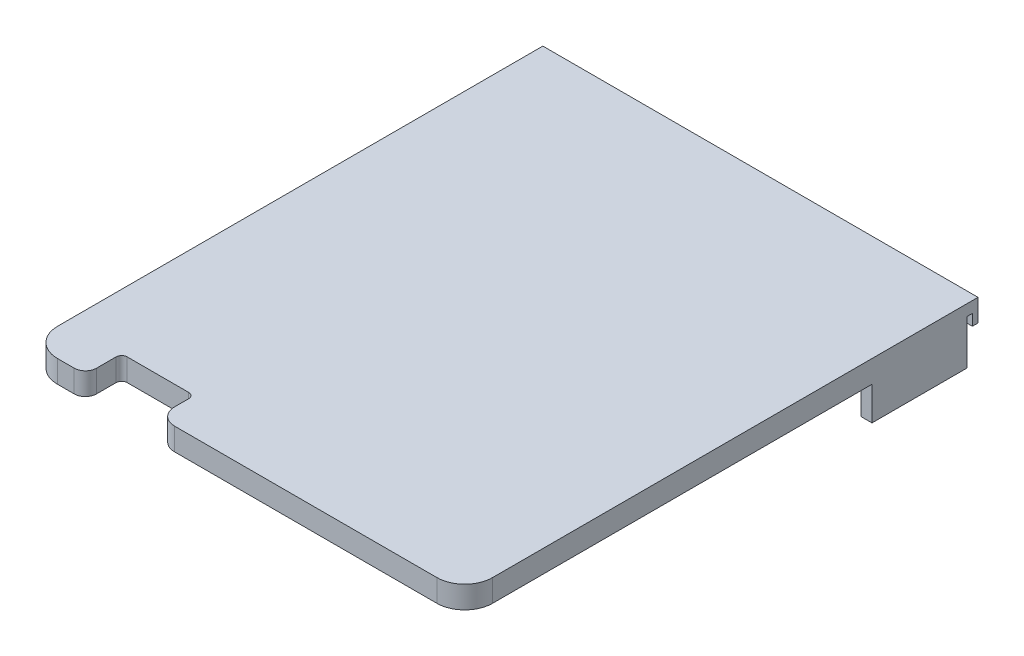
SolidWorks part; units mm, degrees
ref_plane "Спереди" through (0, 0, 0) normal (0, 0, 1) x (1, 0, 0)
ref_plane "Сверху" through (0, 0, 0) normal (0, 1, 0) x (1, 0, 0)
ref_plane "Справа" through (0, 0, 0) normal (1, 0, 0) x (0, 0, -1)
sketch "Эскиз1" plane through (0, 0, 0) normal (0, 1, 0) x (1, 0, 0)
  line L0 (-1049.4217, 39.7729) -> (48950.5783, 39.7729) construction
  line L1 (-1049.4217, 18.7729) -> (48950.5783, 18.7729) construction
  line L2 (-1035.4217, -52.2271) -> (48964.5783, -52.2271) construction
  line L3 (-40.4217, -1047.2271) -> (-40.4217, 48952.7729) construction
  line L4 (-31.4217, -1047.9034) -> (-31.4217, 48952.0966) construction
  line L5 (20.5783, -1057.2271) -> (20.5783, 48942.7729) construction
  line L6 (37.5783, -1047.2271) -> (37.5783, 48952.7729) construction
  line L7 (-49.4217, -981.2271) -> (-49.4217, 49018.7729) construction
  line L8 (46.5783, -981.2271) -> (46.5783, 49018.7729) construction
  line L9 (-1045.358, 38.7729) -> (48954.642, 38.7729) construction
  line L10 (-1045.0307, 37.7729) -> (48954.9693, 37.7729) construction
  line L11 (-48.4217, -971.4559) -> (-48.4217, 49028.5441) construction
  line L12 (-47.4217, -971.3932) -> (-47.4217, 49028.6068) construction
  line L13 (-1037.9024, 19.7729) -> (48962.0976, 19.7729) construction
  line L14 (-1037.2908, 20.7729) -> (48962.7092, 20.7729) construction
  line L16 (45.5783, -974.6284) -> (45.5783, 49025.3716) construction
  line L17 (44.5783, -974.6284) -> (44.5783, 49025.3716) construction
  line L23 (-39.4217, -1000.278) -> (-39.4217, 48999.722) construction
  line L24 (-38.4217, -1000.278) -> (-38.4217, 48999.722) construction
  line L25 (35.5783, -1022.8724) -> (35.5783, 48977.1276) construction
  line L26 (37.5783, -1021.8303) -> (37.5783, 48978.1697) construction
  line L27 (36.5783, -1027.3606) -> (36.5783, 48972.6394) construction
  line L32 (-1031.0615, -51.2271) -> (48968.9385, -51.2271) construction
  line L33 (-1031.4217, -50.2271) -> (48968.5783, -50.2271) construction
  line L34 (-39.4217, 15.7729) -> (-39.4217, -47.2271)
  line L35 (36.5783, -47.2271) -> (36.5783, 15.7729)
  line L47 (-1016.1352, -43.7271) -> (48983.8648, -43.7271) construction
  line L48 (19.5783, -1047.4134) -> (19.5783, 48952.5866) construction
  line L49 (-1004.6212, -44.7271) -> (48995.3788, -44.7271) construction
  line L50 (21.5783, -51.2271) -> (32.5783, -51.2271)
  line L51 (-32.4217, -1036.8679) -> (-32.4217, 48963.1321) construction
  line L52 (-29.0217, -1041.3638) -> (-29.0217, 48958.6362) construction
  line L53 (-16.4217, -1042.1035) -> (-16.4217, 48957.8965) construction
  line L54 (-15.4217, -1048.6999) -> (-15.4217, 48951.3001) construction
  line L57 (21.5783, -51.2271) -> (-14.4217, -51.2271)
  line L58 (-16.4217, -49.2271) -> (-16.4217, -46.7271)
  line L60 (-29.4217, -44.7271) -> (-18.4217, -44.7271)
  line L63 (-35.4217, -51.2271) -> (-32.4217, -51.2271)
  line L64 (-31.4217, -50.2271) -> (-31.4217, -46.7271)
  line L65 (-39.4217, 15.7729) -> (-39.4217, 38.7729)
  line L66 (36.5783, 38.7729) -> (-39.4217, 38.7729)
  line L67 (36.5783, 15.7729) -> (36.5783, 38.7729)
  arc A0 (-32.4217, -51.2271) -> (-31.4217, -50.2271) centre (-32.4217, -50.2271) ccw
  arc A3 (32.5783, -51.2271) -> (36.5783, -47.2271) centre (32.5783, -47.2271) ccw
  arc A5 (-39.4217, -47.2271) -> (-35.4217, -51.2271) centre (-35.4217, -47.2271) ccw
  arc A7 (-31.4217, -46.7271) -> (-29.4217, -44.7271) centre (-29.4217, -46.7271) cw
  arc A8 (-14.4217, -51.2271) -> (-16.4217, -49.2271) centre (-14.4217, -49.2271) cw
  arc A11 (-18.4217, -44.7271) -> (-16.4217, -46.7271) centre (-18.4217, -46.7271) cw
  point P75 (36.5783, -51.2271)
  point P80 (-39.4217, -51.2271)
  point P101 (19.5783, -51.2271)
  point P105 (-32.4217, -50.2271)
  point P106 (20.5783, -50.2271)
  point P108 (20.5783, -43.7271)
  point P109 (-31.4217, -51.2271)
  point P111 (19.5783, -44.7271)
  point P114 (-23.4217, -43.7271)
  point P115 (-32.4217, -43.7271)
  point P117 (-22.4217, -44.7271)
  point P120 (-22.4217, -51.2271)
  point P122 (-31.4217, -44.7271)
  point P123 (-23.4217, -50.2271)
  point P136 (-32.4217, -50.2271)
extrude "Бобышка-Вытянуть1" add sketch "Эскиз1" along normal blind 2
sketch "Эскиз2" plane through (0, 2, 0) normal (0, 1, 0) x (1, 0, 0)
  line L0 (-35.4217, -51.2271) -> (-32.4217, -51.2271)
  line L1 (-31.4217, -50.2271) -> (-31.4217, -46.7271)
  line L2 (-16.4217, -46.7271) -> (-16.4217, -49.2271)
  line L3 (-18.4217, -44.7271) -> (-29.4217, -44.7271)
  line L4 (-14.4217, -51.2271) -> (32.5783, -51.2271)
  line L5 (36.5783, 15.7729) -> (36.5783, -47.2271)
  line L11 (-39.4217, 15.7729) -> (-39.4217, -47.2271)
  line L14 (-40.4217, 15.7729) -> (-40.4217, -47.2271)
  line L15 (-35.4217, -52.2271) -> (-32.4217, -52.2271)
  line L16 (-30.4217, -50.2271) -> (-30.4217, -46.7271)
  line L17 (-18.4217, -45.7271) -> (-29.4217, -45.7271)
  line L18 (-17.4217, -46.7271) -> (-17.4217, -49.2271)
  line L19 (-14.4217, -52.2271) -> (32.5783, -52.2271)
  line L20 (37.5783, 15.7729) -> (37.5783, -47.2271)
  line L24 (-48.4217, 19.7729) -> (-43.4217, 19.7729) construction
  line L25 (-49.4217, 18.7729) -> (-43.4217, 18.7729) construction
  line L26 (-48.4217, 38.7729) -> (-48.4217, 19.7729) construction
  line L27 (-49.4217, 39.7729) -> (-49.4217, 18.7729) construction
  line L28 (40.5783, 19.7729) -> (45.5783, 19.7729) construction
  line L29 (40.5783, 18.7729) -> (46.5783, 18.7729) construction
  line L30 (46.5783, 18.7729) -> (46.5783, 39.7729) construction
  line L31 (45.5783, 19.7729) -> (45.5783, 38.7729) construction
  line L36 (-1039.4217, 38.7729) -> (48960.5783, 38.7729) construction
  line L37 (45.5783, 38.7729) -> (-48.4217, 38.7729) construction
  line L38 (46.5783, 39.7729) -> (-49.4217, 39.7729) construction
  line L39 (-1040.5152, 21.77) -> (48959.4848, 21.77) construction
  line L40 (-40.4217, 15.7729) -> (-40.4217, 21.77)
  line L41 (-40.4217, 21.77) -> (-39.4217, 21.77)
  line L42 (-39.4217, 38.7729) -> (-39.4217, -47.2271) construction
  line L43 (-39.4217, 21.77) -> (-39.4217, 15.7729)
  line L44 (36.5783, 15.7729) -> (36.5783, 21.77)
  line L45 (36.5783, -47.2271) -> (36.5783, 38.7729) construction
  line L46 (36.5783, 21.77) -> (37.5783, 21.77)
  line L47 (37.5783, 21.77) -> (37.5783, 15.7729)
  line L48 (37.5783, 38.7729) -> (37.5783, 39.7729)
  line L49 (-40.4217, 38.7729) -> (-40.4217, 39.7729)
  line L50 (37.5783, 38.7729) -> (-40.4217, 38.7729)
  line L51 (-40.4217, 39.7729) -> (37.5783, 39.7729)
  arc A2 (36.5783, -47.2271) -> (32.5783, -51.2271) centre (32.5783, -47.2271) cw
  arc A3 (-14.4217, -51.2271) -> (-16.4217, -49.2271) centre (-14.4217, -49.2271) cw
  arc A4 (-16.4217, -46.7271) -> (-18.4217, -44.7271) centre (-18.4217, -46.7271) ccw
  arc A5 (-31.4217, -46.7271) -> (-29.4217, -44.7271) centre (-29.4217, -46.7271) cw
  arc A6 (-32.4217, -51.2271) -> (-31.4217, -50.2271) centre (-32.4217, -50.2271) ccw
  arc A7 (-35.4217, -51.2271) -> (-39.4217, -47.2271) centre (-35.4217, -47.2271) cw
  arc A9 (-35.4217, -52.2271) -> (-40.4217, -47.2271) centre (-35.4217, -47.2271) cw
  arc A10 (-32.4217, -52.2271) -> (-30.4217, -50.2271) centre (-32.4217, -50.2271) ccw
  arc A11 (-30.4217, -46.7271) -> (-29.4217, -45.7271) centre (-29.4217, -46.7271) cw
  arc A12 (-17.4217, -46.7271) -> (-18.4217, -45.7271) centre (-18.4217, -46.7271) ccw
  arc A13 (-14.4217, -52.2271) -> (-17.4217, -49.2271) centre (-14.4217, -49.2271) cw
  arc A14 (37.5783, -47.2271) -> (32.5783, -52.2271) centre (32.5783, -47.2271) cw
  arc A16 (-43.4217, 19.7729) -> (-39.4217, 15.7729) centre (-43.4217, 15.7729) cw construction
  arc A17 (-43.4217, 18.7729) -> (-40.4217, 15.7729) centre (-43.4217, 15.7729) cw construction
  arc A18 (40.5783, 18.7729) -> (37.5783, 15.7729) centre (40.5783, 15.7729) ccw construction
  arc A19 (40.5783, 19.7729) -> (36.5783, 15.7729) centre (40.5783, 15.7729) ccw construction
extrude "Бобышка-Вытянуть2" add sketch "Эскиз2" against normal blind 4
sketch "Эскиз3" plane through (0, 2, 0) normal (0, 1, 0) x (1, 0, 0)
  line L1 (-963.4217, 21.77) -> (49036.5783, 21.77) construction
  line L3 (37.5783, -978.23) -> (37.5783, 49021.77) construction
  line L5 (-40.4217, -978.23) -> (-40.4217, 49021.77) construction
  line L26 (-40.4217, 37.7729) -> (-38.4217, 37.7729)
  line L27 (-40.4217, 20.77) -> (-38.4217, 20.77)
  line L28 (35.5783, 37.7729) -> (37.5783, 37.7729)
  line L29 (35.5783, 20.77) -> (37.5783, 20.77)
  line L30 (35.5783, 37.7729) -> (35.5783, 20.77)
  line L31 (37.5783, 20.77) -> (37.5783, 37.7729)
  line L32 (-38.4217, 37.7729) -> (-38.4217, 20.77)
  line L33 (-40.4217, 20.77) -> (-40.4217, 37.7729)
extrude "Бобышка-Вытянуть4" add sketch "Эскиз3" against normal blind 10
sketch "Эскиз5" plane through (0, 2, 0) normal (0, 1, 0) x (1, 0, 0)
  line L0 (-40.4217, 38.7729) -> (-40.4217, 37.7729)
  line L1 (-40.4217, 37.7729) -> (-39.4217, 37.7729)
  line L2 (-39.4217, 37.7729) -> (-39.4217, 38.7729)
  line L3 (-39.4217, 38.7729) -> (-40.4217, 38.7729)
  line L4 (36.5783, 38.7729) -> (36.5783, 37.7729)
  line L5 (37.5783, 37.7729) -> (35.5783, 37.7729) construction
  line L6 (36.5783, 37.7729) -> (37.5783, 37.7729)
  line L7 (37.5783, 37.7729) -> (37.5783, 38.7729)
  line L8 (37.5783, 38.7729) -> (36.5783, 38.7729)
extrude "Бобышка-Вытянуть6" add sketch "Эскиз5" against normal blind 2
